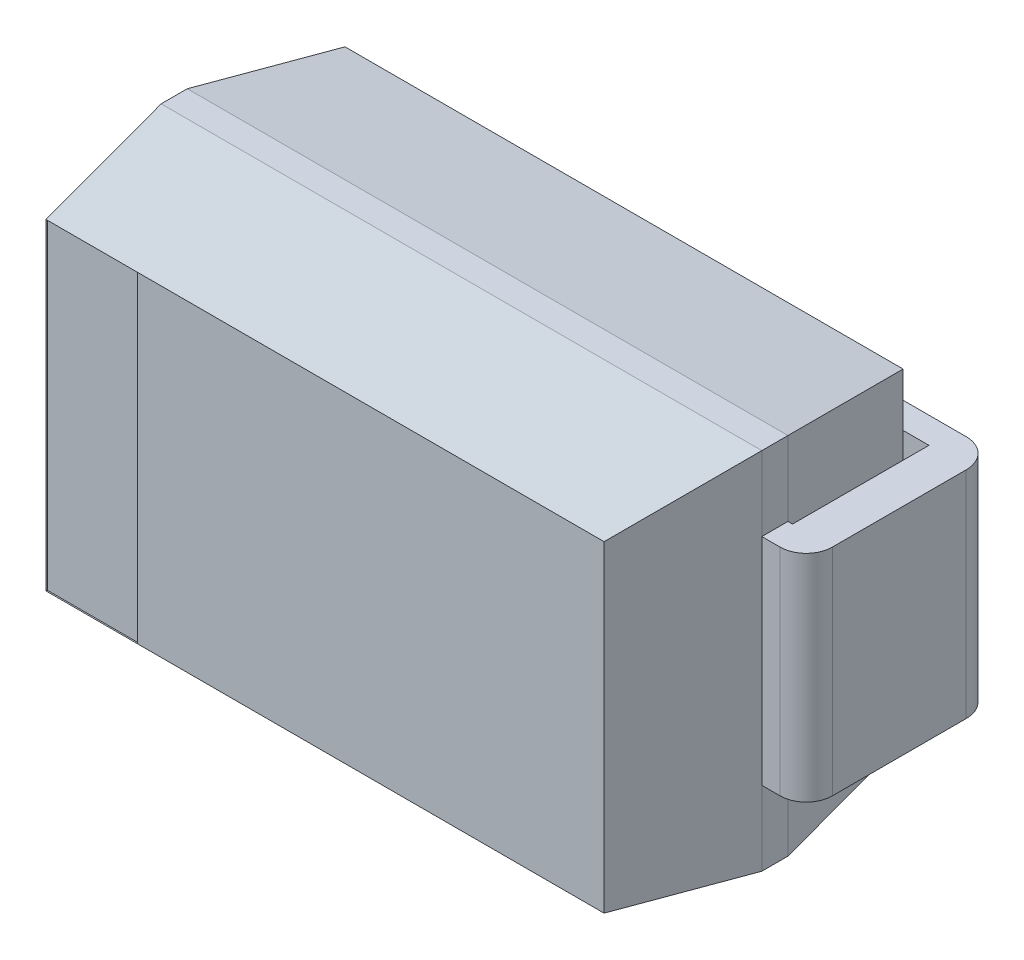
SolidWorks part; units mm, degrees
other "Детальный элемент1"
ref_plane "Спереди" through (0, 0, 0) normal (0, 0, 1) x (1, 0, 0)
ref_plane "Сверху" through (0, 0, 0) normal (0, 1, 0) x (1, 0, 0)
ref_plane "Справа" through (0, 0, 0) normal (1, 0, 0) x (0, 0, -1)
ref_plane "Плоскость1" through (0, 0, 0.2) normal (0, 0, 1) x (1, 0, 0)
sketch "Эскиз1" plane through (0, 0, 0.2) normal (0, 0, 1) x (1, 0, 0)
  line L1 (-2.3, 1.395) -> (2.3, 1.395)
  line L2 (-2.3, 1.395) -> (-2.3, -1.395)
  line L3 (-2.3, -1.395) -> (2.3, -1.395)
  line L4 (2.3, 1.395) -> (2.3, -1.395)
  line L5 (-2.3, 1.395) -> (2.3, -1.395) construction
  line L6 (-2.3, -1.395) -> (2.3, 1.395) construction
  point P0 (0, 0)
  dimension "D1" = 4.6
  dimension "D2" = 2.79
extrude "Бобышка-Вытянуть1" add sketch "Эскиз1" along normal blind 2.29
chamfer "Фаска1" distance 1.045 distance2 0.163 4 edges at (0, 1.395, 2.49) (2.3, 0, 2.49) (0, -1.395, 2.49) (-2.3, 0, 2.49)
chamfer "Фаска2" distance 0.163 distance2 1.045 4 edges at (2.3, 0, 0.2) (0, 1.395, 0.2) (0, -1.395, 0.2) (-2.3, 0, 0.2)
sketch "Эскиз2" plane through (0, 0, 0) normal (0, 1, 0) x (1, 0, 0)
  line L0 (-2.335, -0.2) -> (-2.335, -1.245)
  line L1 (-1.12, 0) -> (-2.42, 0)
  line L2 (-1.12, 0) -> (-1.12, -0.2)
  line L3 (-1.12, -0.2) -> (-2.335, -0.2)
  line L5 (-2.64, -1.245) -> (-2.64, -0.22)
  line L6 (-2.335, -1.245) -> (-2.3, -1.245)
  line L7 (-2.3, -1.245) -> (-2.3, -1.445)
  line L8 (-2.3, -1.445) -> (-2.44, -1.445)
  line L9 (-2.3, -1.445) -> (-2.3, -1.245) construction
  arc A2 (-2.44, -1.445) -> (-2.64, -1.245) centre (-2.44, -1.245) cw
  arc A3 (-2.42, 0) -> (-2.64, -0.22) centre (-2.42, -0.22) ccw
  point P4 (0, 0)
  dimension "D3" = 0.22
  dimension "D5" = 0.2
  dimension "D1" = 0.2
  dimension "D2" = 0.305
  dimension "D4" = 1.52
  dimension "D6" = 0.34
extrude "Бобышка-Вытянуть2" add sketch "Эскиз2" along normal blind 0.825 and the other way blind 0.825 separate body
mirror "Зеркальное отражение1" about plane through (0, 0, 0) normal (1, 0, 0) of bodies 108
sketch "Эскиз3" plane through (0, 0, 2.49) normal (0, 0, 1) x (1, 0, 0)
  line L0 (2.137, 1.232) -> (-2.137, 1.232) construction
  line L1 (-2.137, -1.232) -> (-1.437, -1.232)
  line L2 (-2.137, -1.232) -> (-2.137, 1.232)
  line L3 (-2.137, 1.232) -> (-1.437, 1.232)
  line L4 (-1.437, -1.232) -> (-1.437, 1.232)
  dimension "D1" = 0.7
extrude "Вырез-Вытянуть1" cut sketch "Эскиз3" against normal blind 0.01
